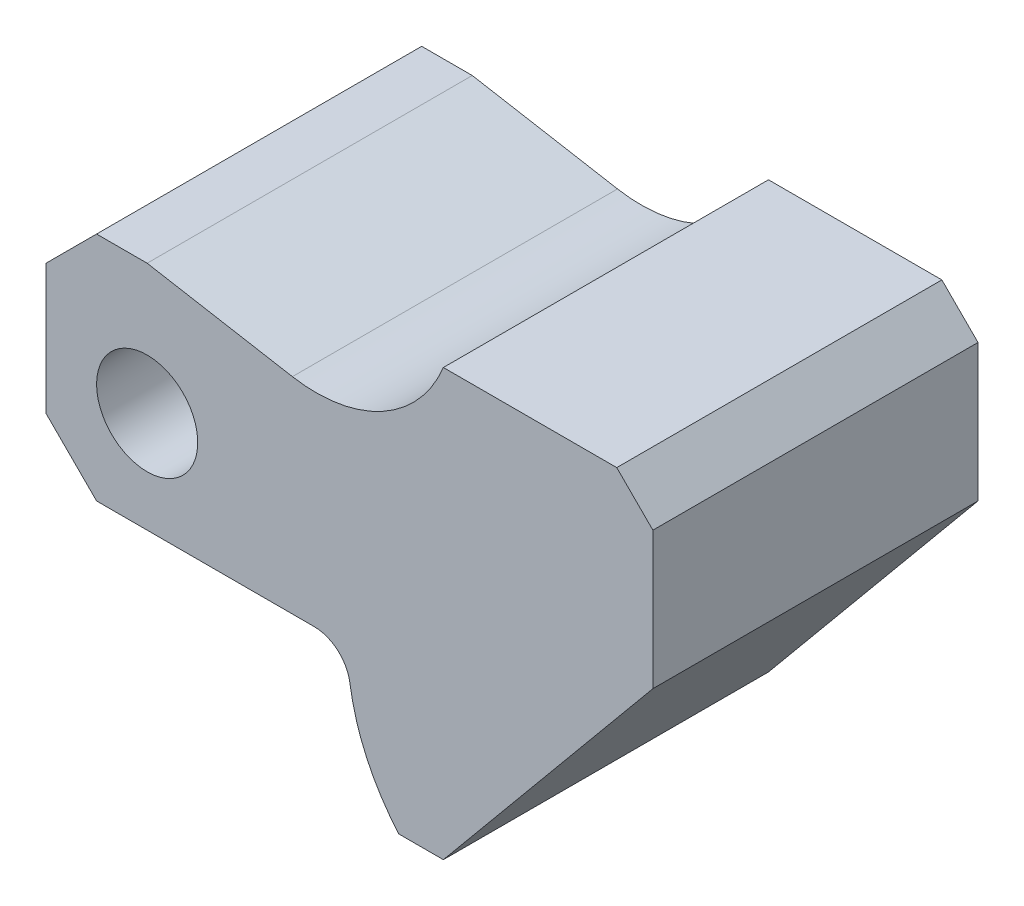
SolidWorks part; units mm, degrees
material "AISI 1020"
ref_plane "Plan de face" through (0, 0, 0) normal (0, 0, 1) x (1, 0, 0)
ref_plane "Plan de dessus" through (0, 0, 0) normal (0, 1, 0) x (1, 0, 0)
ref_plane "Plan de droite" through (0, 0, 0) normal (1, 0, 0) x (0, 0, -1)
sketch "Esquisse1" plane through (0, 0, 0) normal (0, 0, 1) x (1, 0, 0)
  line L0 (38.0103, -3.2308) -> (62.0103, -3.2308)
  line L1 (62.0103, -3.2308) -> (67.0103, -8.2308)
  line L2 (67.0103, -8.2308) -> (67.0103, -27.2308)
  line L3 (67.0103, -27.2308) -> (38.0103, -62.2308)
  line L4 (38.0103, -62.2308) -> (31.8443, -62.2308)
  line L6 (20.1228, -43.2308) -> (-9.9897, -43.2308)
  line L7 (-9.9897, -43.2308) -> (-16.9897, -36.2308)
  line L8 (-16.9897, -36.2308) -> (-16.9897, -18.2308)
  line L9 (-16.9897, -18.2308) -> (-9.9897, -11.2308)
  line L12 (-9.9897, -11.2308) -> (-2.9897, -11.2308)
  line L18 (-2.9897, -11.2308) -> (17.1143, -14.7757)
  arc A1 (25.0685, -47.4955) -> (20.1228, -43.2308) centre (20.1228, -48.2308) ccw
  arc A2 (38.0103, -3.2308) -> (17.1143, -14.7757) centre (20.4137, 3.9356) cw
  arc A3 (31.8443, -62.2308) -> (25.0685, -47.4955) centre (53.7532, -43.2308) cw
  circle A4 centre (-2.9897, -29.2308) radius 7
  point P17 (24.1901, -43.2308)
  dimension "D15" = 5
  dimension "D17" = 29
  dimension "D1" = 29
  dimension "D2" = 24
  dimension "D3" = 59
  dimension "D4" = 5
  dimension "D5" = 7
  dimension "D6" = 32
  dimension "D7" = 7
  dimension "D8" = 19
  dimension "D10" = 135
  dimension "D11" = 84
  dimension "D13" = 135
  dimension "D12" = 14
  dimension "D14" = 29
  dimension "D16" = 190
  dimension "D18" = 14
  dimension "D19" = 14
  dimension "D20" = 135
  dimension "D9" = 19
  dimension "D21" = 19
extrude "Boss.-Extru.2" add sketch "Esquisse1" along normal blind 45
equation "\"A\" = 84"
equation "\"B\" = 59"
equation "\"C\" = 45"
equation "\"D11@Esquisse1\"=\"A\""
equation "\"D3@Esquisse1\"=\"B\""
equation "\"D1@Boss.-Extru.2\"=\"C\""
